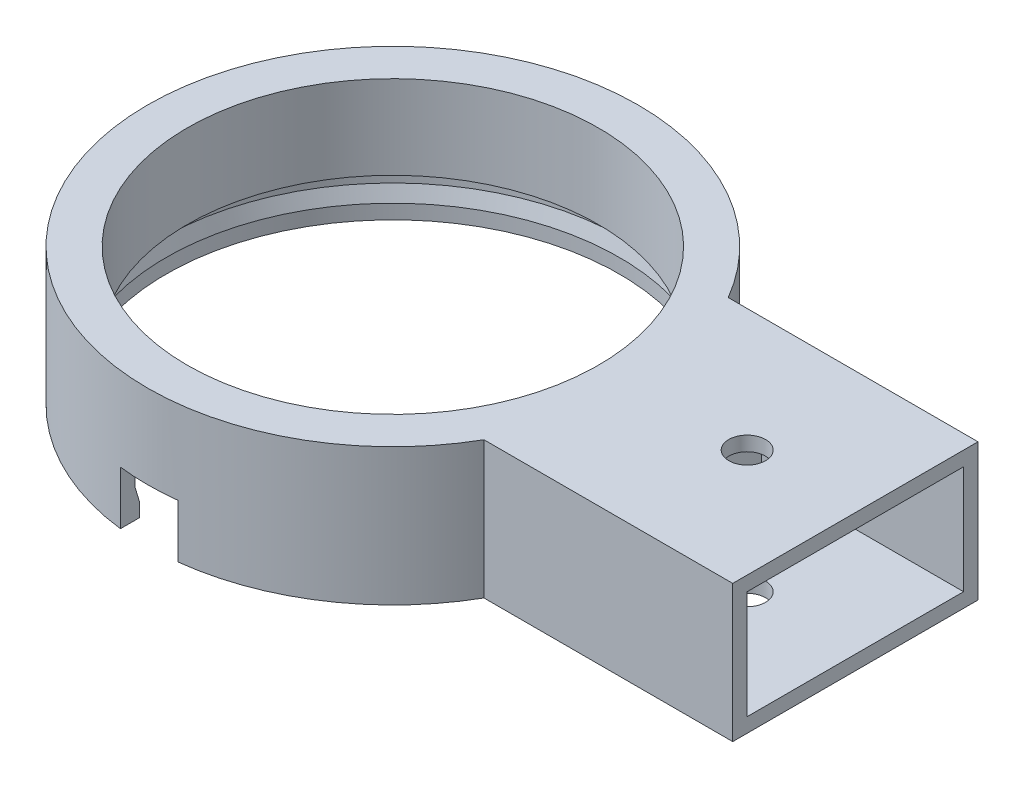
SolidWorks part; units mm, degrees
ref_plane "Front Plane" through (0, 0, 0) normal (0, 0, 1) x (1, 0, 0)
ref_plane "Top Plane" through (0, 0, 0) normal (0, 1, 0) x (1, 0, 0)
ref_plane "Right Plane" through (0, 0, 0) normal (1, 0, 0) x (0, 0, -1)
sketch "Sketch1" plane through (0, 0, 0) normal (0, 1, 0) x (1, 0, 0)
  circle A0 centre (0, 0) radius 38.1
  circle A1 centre (0, 0) radius 36.195
  circle A2 centre (0, 0) radius 43.18
  dimension "D1" = 76.2
  dimension "D2" = 72.39
  dimension "D3" = 86.36
extrude "Boss-Extrude1" add sketch "Sketch1" along normal blind 2.54 contours A2 A0 | A0 A1
sketch "Sketch2" plane through (0, 0, 0) normal (0, -1, 0) x (1, 0, 0)
  circle A0 centre (0, 0) radius 40.64
  circle A2 centre (0, 0) radius 43.18
  dimension "D1" = 81.28
extrude "Boss-Extrude2" add sketch "Sketch2" along normal blind 4.318
sketch "Sketch3" plane through (0, 0, 0) normal (0, 0, 1) x (1, 0, 0)
  line L0 (0, 0) -> (-40.64, 0)
  line L1 (-40.64, 0) -> (-40.64, -4.318)
  line L2 (-39.878, -4.318) -> (-39.878, -6.858)
  line L3 (-40.64, -4.318) -> (-39.878, -6.858)
  line L4 (-40.64, -4.318) -> (-39.878, -4.318)
  line L5 (-39.878, -6.858) -> (-39.878, -9.398)
  line L6 (-39.878, -9.398) -> (-43.18, -9.398)
  line L7 (-40.64, -4.318) -> (-43.18, -4.318)
  line L8 (-43.18, -4.318) -> (-43.18, -9.398)
  line L9 (0, 0) -> (0, 20.6505)
  dimension "D1" = 40.64
  dimension "D2" = 4.318
  dimension "D3" = 0.762
  dimension "D4" = 2.54
  dimension "D5" = 2.54
  dimension "D6" = 3.302
  dimension "D7" = 2.54
revolve "Revolve1" add sketch "Sketch3" angle 360 about L9
ref_plane "Plane1" through (0, 0, 43.18) normal (0, 0, 1) x (1, 0, 0)
sketch "Sketch7" plane through (0, 0, 43.18) normal (0, 0, 1) x (1, 0, 0)
  line L0 (0, -10.16) -> (0, 0)
  line L1 (0, 0) -> (5.08, 0)
  line L2 (5.08, 0) -> (5.08, -10.16)
  line L3 (43.18, 2.54) -> (-43.18, 2.54) construction
  line L4 (0, 0) -> (-5.08, 0)
  line L5 (-5.08, 0) -> (-5.08, -10.16)
  line L6 (5.08, -10.16) -> (-5.08, -10.16)
  dimension "D1" = 5.08
  dimension "D2" = 10.16
  dimension "D3" = 10.16
  dimension "D4" = 2.54
  dimension "D5" = 5.08
extrude "Cut-Extrude1" cut sketch "Sketch7" against normal blind 12.7 contours L6 L0 L4 L5 | L6 L2 L1 L0
ref_plane "Plane2" through (43.18, 0, 0) normal (1, 0, 0) x (0, 0, -1)
sketch "Sketch8" plane through (43.18, 0, 0) normal (1, 0, 0) x (0, 0, -1)
  line L0 (0.1499, -9.398) -> (21.7399, -9.398)
  line L1 (-42.8801, -9.398) -> (43.18, -9.398) construction
  line L2 (21.7399, -9.398) -> (21.7399, 14.732)
  line L3 (21.7399, 14.732) -> (-21.4401, 14.732)
  line L4 (-21.4401, 14.732) -> (-21.4401, -9.398)
  line L5 (-21.4401, -9.398) -> (0.1499, -9.398)
  dimension "D1" = 24.13
  dimension "D2" = 21.59
  dimension "D3" = 21.59
sketch "Sketch12" plane through (0, 2.54, 0) normal (0, 1, 0) x (1, 0, 0)
  circle A0 centre (0, 0) radius 36.195
  circle A1 centre (0, 0) radius 43.18
extrude "Boss-Extrude3" add sketch "Sketch12" along normal blind 12.192
extrude "Boss-Extrude4" add sketch "Sketch8" against normal up to body contours L4 L5 L0 L2 L3
sketch "Sketch13" plane through (43.18, 0, 0) normal (1, 0, 0) x (0, 0, -1)
  line L0 (-21.4401, 14.732) -> (21.7399, 14.732)
  line L1 (21.7399, 14.732) -> (21.7399, -9.398)
  line L2 (21.7399, -9.398) -> (-21.4401, -9.398)
  line L3 (-21.4401, -9.398) -> (-21.4401, 14.732)
extrude "Boss-Extrude5" add sketch "Sketch13" along normal blind 38.1
sketch "Sketch14" plane through (81.28, 0, 0) normal (1, 0, 0) x (0, 0, -1)
  line L14 (-18.9001, 12.192) -> (-18.9001, -6.858)
  line L15 (-18.9001, -6.858) -> (19.1999, -6.858)
  line L16 (19.1999, -6.858) -> (19.1999, 12.192)
  line L17 (19.1999, 12.192) -> (-18.9001, 12.192)
  line L18 (-18.9001, 12.192) -> (-18.9001, -6.858)
  line L19 (-18.9001, -6.858) -> (19.1999, -6.858)
  line L20 (19.1999, -6.858) -> (19.1999, 12.192)
  line L21 (19.1999, 12.192) -> (-18.9001, 12.192)
  dimension "D1" = 2.54
extrude "Cut-Extrude2" cut sketch "Sketch14" against normal blind 35.56
sketch "Sketch17" plane through (0, 14.732, 0) normal (0, 1, 0) x (1, 0, 0)
  line L0 (81.28, 21.7399) -> (81.28, 0.1499)
  line L1 (81.28, 21.7399) -> (81.28, -21.4401) construction
  line L2 (81.28, 0.1499) -> (62.23, 0.1499)
  circle A0 centre (62.23, 0.1499) radius 3.2385
  dimension "D2" = 6.477
  dimension "D1" = 19.05
extrude "Cut-Extrude3" cut sketch "Sketch17" against normal blind 35.56
